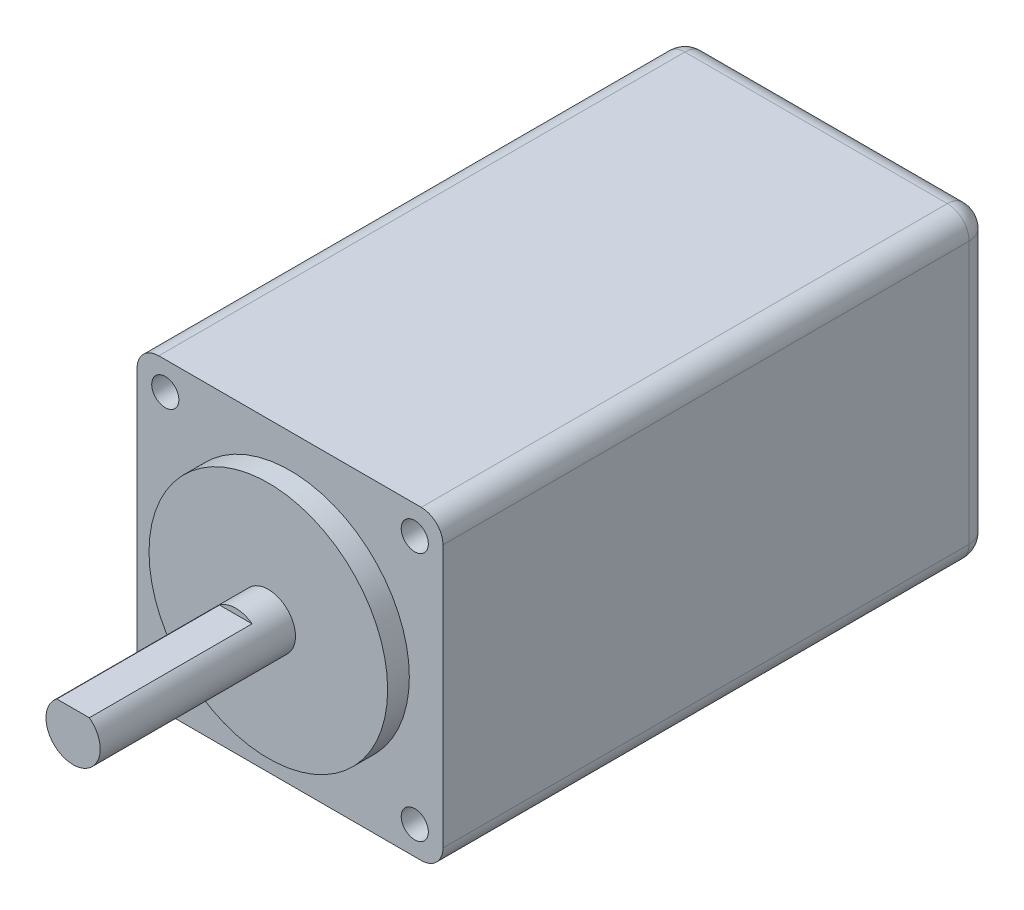
SolidWorks part; units mm, degrees
ref_plane "Front Plane" through (0, 0, 0) normal (0, 0, 1) x (1, 0, 0)
ref_plane "Top Plane" through (0, 0, 0) normal (0, 1, 0) x (1, 0, 0)
ref_plane "Right Plane" through (0, 0, 0) normal (1, 0, 0) x (0, 0, -1)
sketch "Sketch1" plane through (0, 0, 0) normal (0, 0, 1) x (1, 0, 0)
  line L1 (-14.1, -14.1) -> (14.1, -14.1)
  line L2 (-14.1, -14.1) -> (-14.1, 14.1)
  line L3 (-14.1, 14.1) -> (14.1, 14.1)
  line L4 (14.1, -14.1) -> (14.1, 14.1)
  line L5 (-14.1, -14.1) -> (14.1, 14.1) construction
  line L6 (-14.1, 14.1) -> (14.1, -14.1) construction
  point P0 (0, 0)
  dimension "D1" = 28.2
  dimension "D2" = 28.2
extrude "Boss-Extrude1" add sketch "Sketch1" along normal blind 50.5
sketch "Sketch2" plane through (0, 0, 50.5) normal (0, 0, 1) x (1, 0, 0)
  circle A0 centre (0, 0) radius 11
  dimension "D1" = 22
extrude "Boss-Extrude2" add sketch "Sketch2" along normal blind 2
sketch "Sketch3" plane through (0, 0, 52.5) normal (0, 0, 1) x (1, 0, 0)
  circle A0 centre (0, 0) radius 2.5
  dimension "D1" = 5
extrude "Boss-Extrude3" add sketch "Sketch3" along normal blind 18
sketch "Sketch4" plane through (0, 0, 0) normal (1, 0, 0) x (0, 0, -1)
  line L1 (-70.5, 2.5) -> (-55.5, 2.5)
  line L2 (-70.5, 2.5) -> (-70.5, 2)
  line L3 (-70.5, 2) -> (-55.5, 2)
  line L4 (-55.5, 2.5) -> (-55.5, 2)
  dimension "D1" = 15
  dimension "D2" = 0.5
extrude "Cut-Extrude1" cut sketch "Sketch4" against normal mid plane 10
sketch "Sketch5" plane through (0, 0, 50.5) normal (0, 0, 1) x (1, 0, 0)
  line L1 (-11.5, -11.5) -> (11.5, -11.5) construction
  line L2 (-11.5, -11.5) -> (-11.5, 11.5) construction
  line L3 (-11.5, 11.5) -> (11.5, 11.5) construction
  line L4 (11.5, -11.5) -> (11.5, 11.5) construction
  line L5 (-11.5, -11.5) -> (11.5, 11.5) construction
  line L6 (-11.5, 11.5) -> (11.5, -11.5) construction
  circle A0 centre (-11.5, 11.5) radius 1.25
  circle A1 centre (11.5, 11.5) radius 1.25
  circle A2 centre (11.5, -11.5) radius 1.25
  circle A3 centre (-11.5, -11.5) radius 1.25
  point P0 (0, 0)
  dimension "D3" = 2.5
  dimension "D1" = 23
  dimension "D2" = 23
  dimension "D4" = 4
extrude "Cut-Extrude2" cut sketch "Sketch5" against normal blind 2.5
fillet "Fillet1" radius 2 8 edges at (0, 14.1, 0) (-14.1, 0, 0) (0, -14.1, 0) (14.1, 0, 0) (-14.1, -14.1, 25.25) (14.1, -14.1, 25.25) (-14.1, 14.1, 25.25) (14.1, 14.1, 25.25)
